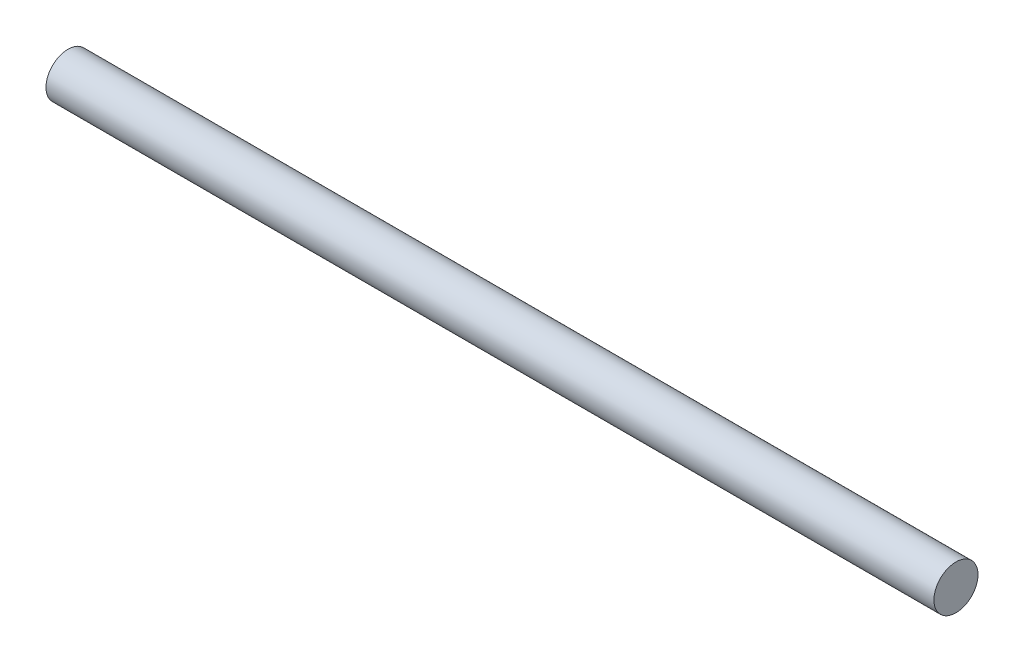
SolidWorks part; units mm, degrees
ref_plane "Plan de face" through (0, 0, 0) normal (0, 0, 1) x (1, 0, 0)
ref_plane "Plan de dessus" through (0, 0, 0) normal (0, 1, 0) x (1, 0, 0)
ref_plane "Plan de droite" through (0, 0, 0) normal (1, 0, 0) x (0, 0, -1)
sketch "Esquisse1" plane through (0, 0, 0) normal (1, 0, 0) x (0, 0, -1)
  circle A0 centre (0, 0) radius 3.5
  dimension "D1" = 7
extrude "Boss.-Extru.1" add sketch "Esquisse1" along normal blind 141 contours A0
